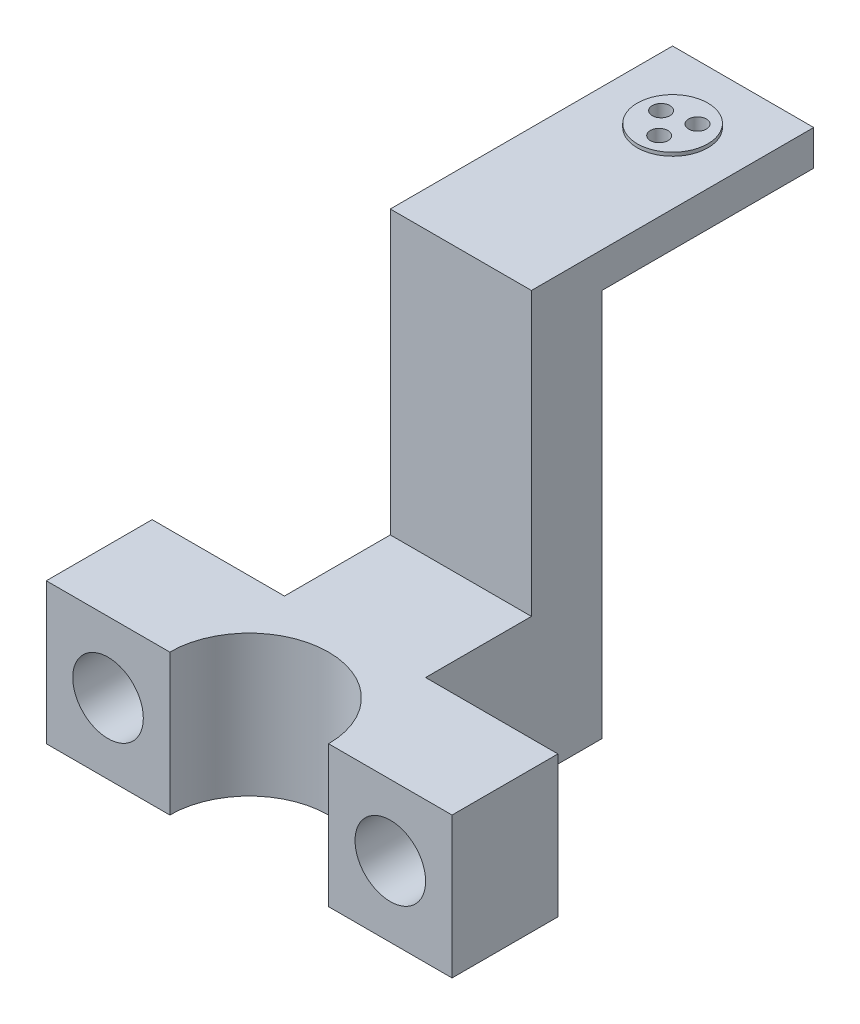
SolidWorks part; units mm, degrees
ref_plane "Front Plane" through (0, 0, 0) normal (0, 0, 1) x (1, 0, 0)
ref_plane "Top Plane" through (0, 0, 0) normal (0, 1, 0) x (1, 0, 0)
ref_plane "Right Plane" through (0, 0, 0) normal (1, 0, 0) x (0, 0, -1)
sketch "Sketch2" plane through (0, 0, 0) normal (0, 0, 1) x (1, 0, 0)
  line L1 (-59.6296, 43.5053) -> (55.3704, 43.5053)
  line L2 (-59.6296, 43.5053) -> (-59.6296, 3.5053)
  line L3 (-59.6296, 3.5053) -> (55.3704, 3.5053)
  line L4 (55.3704, 43.5053) -> (55.3704, 3.5053)
  dimension "D1" = 115
  dimension "D2" = 40
extrude "Boss-Extrude1" add sketch "Sketch2" along normal blind 60
sketch "Sketch3" plane through (0, 43.5053, 0) normal (0, 1, 0) x (1, 0, 0)
  line L0 (-59.6296, -60) -> (-59.6296, 0) construction
  line L1 (-59.6296, -30) -> (-24.6296, -30)
  line L2 (-59.6296, -30) -> (-59.6296, -60)
  line L3 (-59.6296, -60) -> (55.3704, -60)
  line L4 (55.3704, -30) -> (55.3704, -60)
  line L5 (20.3704, -30) -> (55.3704, -30)
  arc A0 (20.3704, -30) -> (-24.6296, -30) centre (-2.1296, -30) ccw
  dimension "D1" = 35
  dimension "D3" = 22.5
  dimension "D2" = 35
  dimension "D4" = 45
extrude "Cut-Extrude1" cut sketch "Sketch3" against normal blind 60
sketch "Sketch4" plane through (0, 0, 30) normal (0, 0, 1) x (1, 0, 0)
  line L0 (-24.6296, 3.5053) -> (-59.6296, 3.5053) construction
  line L1 (-59.6296, 3.5053) -> (-59.6296, 43.5053) construction
  line L2 (55.3704, 3.5053) -> (55.3704, 43.5053) construction
  line L3 (55.3704, 3.5053) -> (20.3704, 3.5053) construction
  circle A0 centre (-42.1296, 23.5053) radius 10
  circle A1 centre (37.8704, 23.5053) radius 10
  dimension "D1" = 20
  dimension "D3" = 17.5
  dimension "D2" = 17.5
  dimension "D4" = 20
  dimension "D5" = 80
extrude "Cut-Extrude2" cut sketch "Sketch4" against normal blind 60
sketch "Sketch5" plane through (0, 0, 0) normal (0, 0, -1) x (-1, 0, 0)
  line L0 (-55.3704, 43.5053) -> (59.6296, 43.5053) construction
  line L1 (-17.8704, 43.5053) -> (22.1296, 43.5053)
  line L2 (-17.8704, 43.5053) -> (-17.8704, 3.5053)
  line L3 (-17.8704, 3.5053) -> (22.1296, 3.5053)
  line L4 (22.1296, 43.5053) -> (22.1296, 3.5053)
  line L5 (59.6296, 3.5053) -> (-55.3704, 3.5053) construction
  circle A0 centre (-37.8704, 23.5053) radius 10 construction
  circle A1 centre (42.1296, 23.5053) radius 10 construction
  dimension "D1" = 20
  dimension "D2" = 20
  dimension "D3" = 40
extrude "Boss-Extrude2" add sketch "Sketch5" along normal blind 50
sketch "Sketch6" plane through (0, 43.5053, 0) normal (0, 1, 0) x (1, 0, 0)
  line L0 (-22.1296, 50) -> (-22.1296, 0) construction
  line L1 (-22.1296, 30) -> (17.8704, 30)
  line L2 (-22.1296, 30) -> (-22.1296, 50)
  line L3 (-22.1296, 50) -> (17.8704, 50)
  line L4 (17.8704, 30) -> (17.8704, 50)
  dimension "D1" = 20
extrude "Boss-Extrude3" add sketch "Sketch6" along normal blind 70
sketch "Sketch7" plane through (0, 113.5053, 0) normal (0, 1, 0) x (1, 0, 0)
  line L1 (-22.1296, 30) -> (17.8704, 30)
  line L2 (-22.1296, 30) -> (-22.1296, 110)
  line L3 (-22.1296, 110) -> (17.8704, 110)
  line L4 (17.8704, 30) -> (17.8704, 110)
  dimension "D1" = 80
extrude "Boss-Extrude4" add sketch "Sketch7" along normal blind 10
sketch "Sketch9" plane through (0, 123.5053, 0) normal (0, 1, 0) x (1, 0, 0)
  line L0 (17.8704, 30) -> (17.8704, 110) construction
  line L1 (-22.1296, 110) -> (-22.1296, 30) construction
  line L2 (17.8704, 110) -> (-22.1296, 110) construction
  circle A0 centre (-2.1296, 90) radius 10
  point P8 (-2.1296, 110)
  dimension "D1" = 20
  dimension "D2" = 20
  dimension "D4" = 20
  dimension "D3" = 20
extrude "Boss-Extrude5" add sketch "Sketch9" along normal blind 1
sketch "Sketch10" plane through (0, 124.5053, 0) normal (0, 1, 0) x (1, 0, 0)
  circle A0 centre (-6.8969, 91.5076) radius 2.5
  circle A1 centre (-2.1296, 90) radius 10 construction
  circle A2 centre (1.5596, 93.3748) radius 2.5
  circle A3 centre (-1.0516, 85.1176) radius 2.5
  dimension "D1" = 5
  dimension "D2" = 5
  dimension "D3" = 3
extrude "Cut-Extrude3" cut sketch "Sketch10" against normal blind 15
